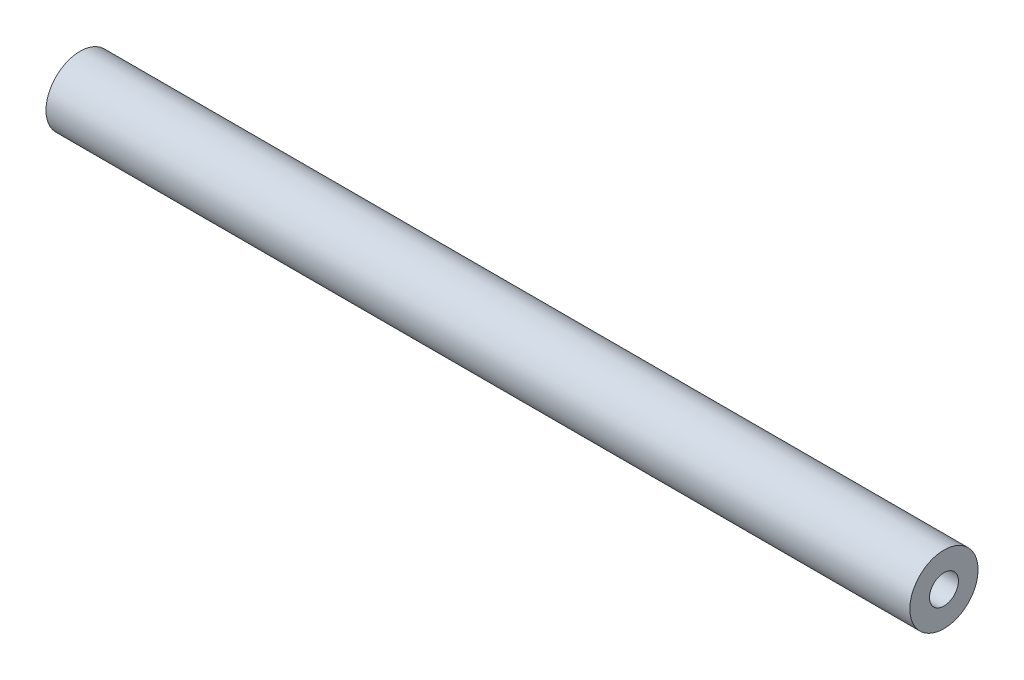
SolidWorks part; units mm, degrees
material "6061-T6 (SS)"
ref_plane "Front Plane" through (0, 0, 0) normal (0, 0, 1) x (1, 0, 0)
ref_plane "Top Plane" through (0, 0, 0) normal (0, 1, 0) x (1, 0, 0)
ref_plane "Right Plane" through (0, 0, 0) normal (1, 0, 0) x (0, 0, -1)
sketch "Sketch1" plane through (0, 0, 0) normal (1, 0, 0) x (0, 0, -1)
  circle A0 centre (0, 0) radius 4.7625
  dimension "D1" = 9.525
extrude "Boss-Extrude1" add sketch "Sketch1" along normal mid plane 120.65
hole_wizard "#10-32 Tapped Hole1" positions "3DSketch1" profile "Sketch2" tap size "#10-32" standard "ANSI Inch"
sketch3d "3DSketch1"
  line L0 (60.325, 0, 0) -> (-60.325, 0, 0) construction
  point P0 (60.325, 0, 0)
  point P4 (-60.325, 0, 0)
sketch "Sketch2" plane through (60.325, 0, 0) normal (0, 1, 0) x (0, 0, -1)
  line L0 (0, 0) -> (0, 17.4693)
  line L1 (0, 17.4693) -> (2.0193, 16.256)
  line L2 (2.0193, 16.256) -> (2.0193, 0)
  line L5 (2.0193, 0) -> (0, 0)
  line L10 (0, 17.4693) -> (-2.0193, 16.256) construction
  line L11 (0, -6.35) -> (0, 107.95) construction
  dimension "Tap Drill Dia." = 4.0386
  dimension "Tap Drill Depth" = 16.256
  dimension "Drill Angle" = 118
cosmetic thread "Hole Thread1"
cosmetic thread "Hole Thread2"
